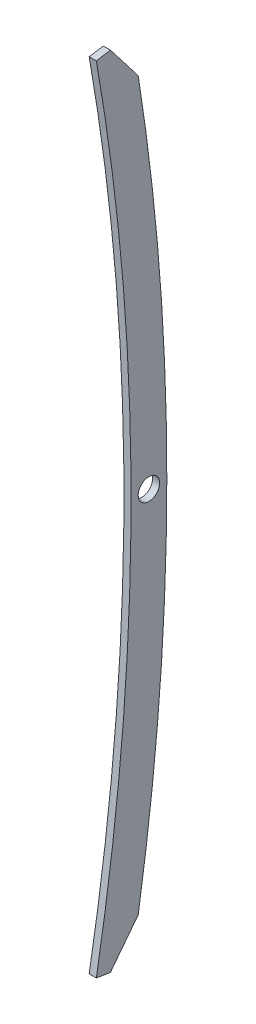
SolidWorks part; units mm, degrees
ref_plane "Front Plane" through (0, 0, 0) normal (1, 0, 0) x (0, 1, 0)
ref_plane "Top Plane" through (0, 0, 0) normal (0, 0, 1) x (0, 1, 0)
ref_plane "Right Plane" through (0, 0, 0) normal (0, 1, 0) x (-1, 0, 0)
sketch "Sketch1" plane through (0, 0, 0) normal (1, 0, 0) x (0, 1, 0)
  line L0 (0, 0) -> (0, -812.8) construction
  line L4 (0, -812.8) -> (0, -825.5) construction
  line L5 (0, 0) -> (141.1412, -800.4517) construction
  line L6 (0, 0) -> (129.1367, -815.3367) construction
  line L7 (141.1412, -800.4517) -> (141.9359, -805.4692)
  line L8 (141.9359, -805.4692) -> (129.1367, -815.3367)
  line L9 (-141.9359, -805.4692) -> (-129.1367, -815.3367)
  line L10 (-141.1412, -800.4517) -> (-141.9359, -805.4692)
  circle A2 centre (0, 0) radius 812.8 construction
  circle A3 centre (0, 0) radius 825.5 construction
  arc A4 (-141.1412, -800.4517) -> (141.1412, -800.4517) centre (0, 0) ccw
  arc A5 (-129.1367, -815.3367) -> (129.1367, -815.3367) centre (0, 0) ccw
  circle A6 centre (0, -819.15) radius 3.81
  dimension "D1" = 812.8
  dimension "D2" = 12.7
  dimension "D3" = 10
  dimension "D6" = 7.62
  dimension "D4" = 9
  dimension "D5" = 5.08
extrude "Boss-Extrude1" add sketch "Sketch1" along normal mid plane 2.54
